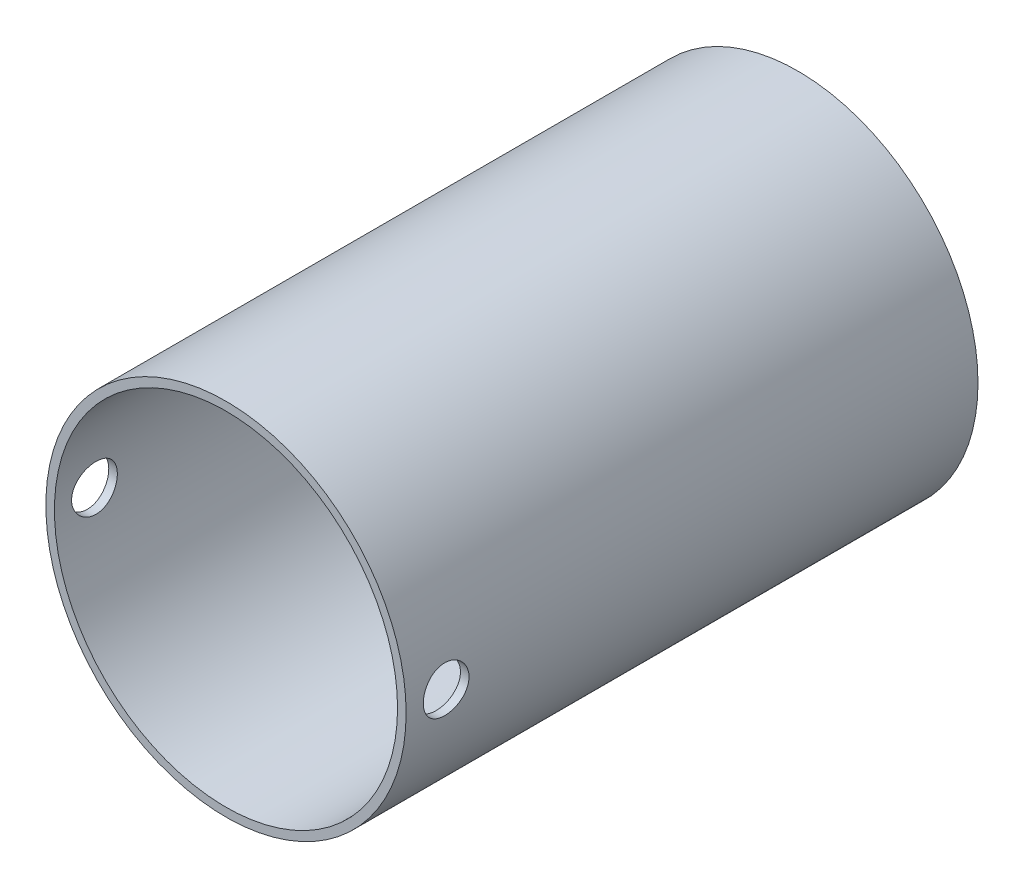
SolidWorks part; units mm, degrees
ref_plane "Alzado" through (0, 0, 0) normal (0, 0, 1) x (1, 0, 0)
ref_plane "Planta" through (0, 0, 0) normal (0, 1, 0) x (1, 0, 0)
ref_plane "Vista lateral" through (0, 0, 0) normal (1, 0, 0) x (0, 0, -1)
sketch "Croquis1" plane through (0, 0, 0) normal (0, 0, 1) x (1, 0, 0)
  circle A0 centre (0, 0) radius 30
  circle A1 centre (0, 0) radius 31.5
  dimension "D1" = 63
  dimension "D2" = 1.5
extrude "Saliente-Extruir1" add sketch "Croquis1" along normal blind 100
sketch "Croquis2" plane through (0, 0, 0) normal (1, 0, 0) x (0, 0, -1)
  line L1 (-100, 31.5) -> (-100, -31.5) construction
  circle A0 centre (-93, 0) radius 4
  dimension "D1" = 8
  dimension "D2" = 7
extrude "Cortar-Extruir1" cut sketch "Croquis2" against normal through all and the other way through all
